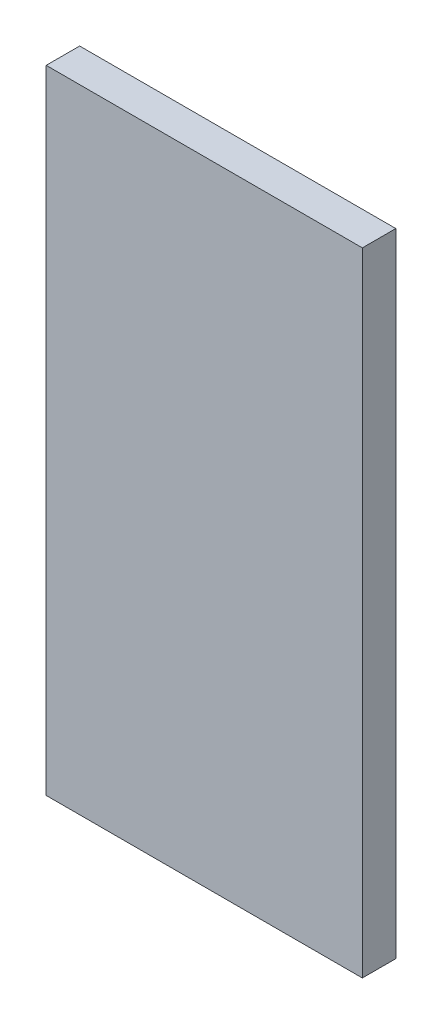
SolidWorks part; units mm, degrees
ref_plane "Front" through (0, 0, 0) normal (0, 0, 1) x (1, 0, 0)
ref_plane "Top" through (0, 0, 0) normal (0, 1, 0) x (1, 0, 0)
ref_plane "Right" through (0, 0, 0) normal (1, 0, 0) x (0, 0, -1)
sketch "Sketch1" plane through (0, 0, 0) normal (0, 0, 1) x (1, 0, 0)
  line L1 (-7.5, -15) -> (7.5, -15)
  line L2 (-7.5, -15) -> (-7.5, 15)
  line L3 (-7.5, 15) -> (7.5, 15)
  line L4 (7.5, -15) -> (7.5, 15)
  line L5 (-7.5, -15) -> (7.5, 15) construction
  line L6 (-7.5, 15) -> (7.5, -15) construction
  point P0 (0, 0)
  dimension "D1" = 15
  dimension "D2" = 30
extrude "Boss-Extrude1" add sketch "Sketch1" along normal mid plane 1.5875
